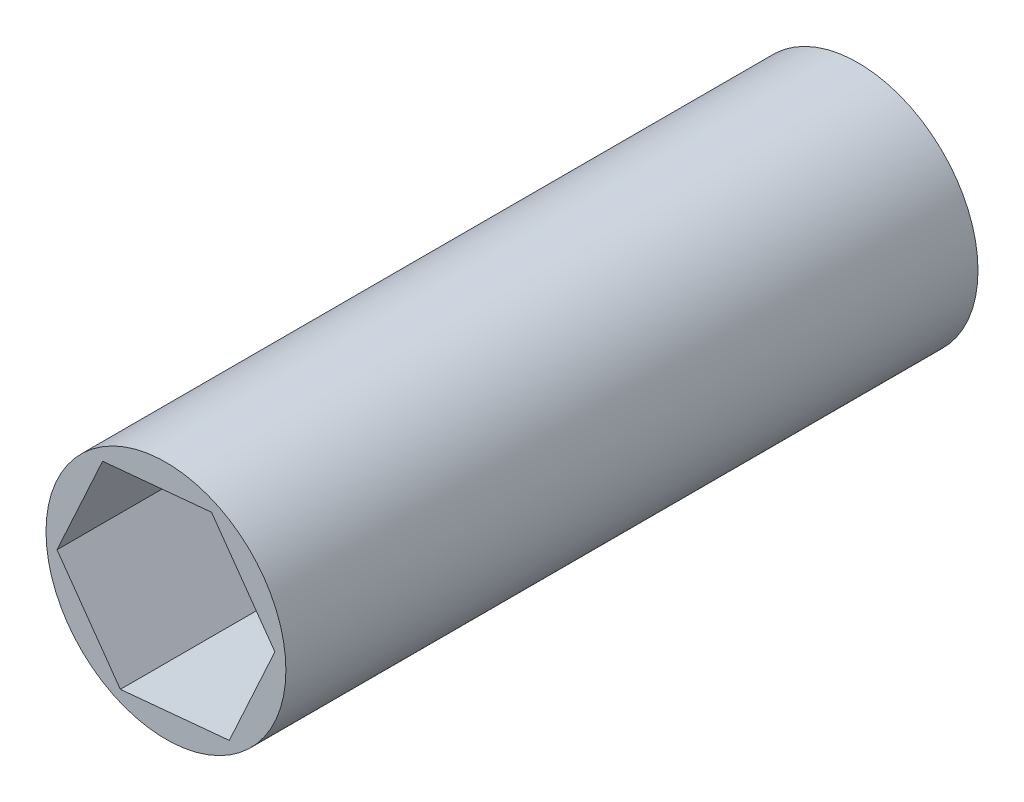
SolidWorks part; units mm, degrees
material "ABS"
ref_plane "Front Plane" through (0, 0, 0) normal (0, 0, 1) x (1, 0, 0)
ref_plane "Top Plane" through (0, 0, 0) normal (0, 1, 0) x (1, 0, 0)
ref_plane "Right Plane" through (0, 0, 0) normal (1, 0, 0) x (0, 0, -1)
sketch "Sketch1" plane through (0, 0, 0) normal (0, 0, 1) x (1, 0, 0)
  line L1 (-3.3539, 4.7228) -> (-5.767, -0.5431)
  line L2 (-5.767, -0.5431) -> (-2.4131, -5.266)
  line L3 (-2.4131, -5.266) -> (3.3539, -4.7228)
  line L4 (3.3539, -4.7228) -> (5.767, 0.5431)
  line L5 (5.767, 0.5431) -> (2.4131, 5.266)
  line L6 (2.4131, 5.266) -> (-3.3539, 4.7228)
  circle A0 centre (0, 0) radius 5.0165 construction
  circle A1 centre (0, 0) radius 6.35
  dimension "D2" = 12.7
  dimension "D1" = 10.033
extrude "Boss-Extrude1" add sketch "Sketch1" along normal blind 36.6395
